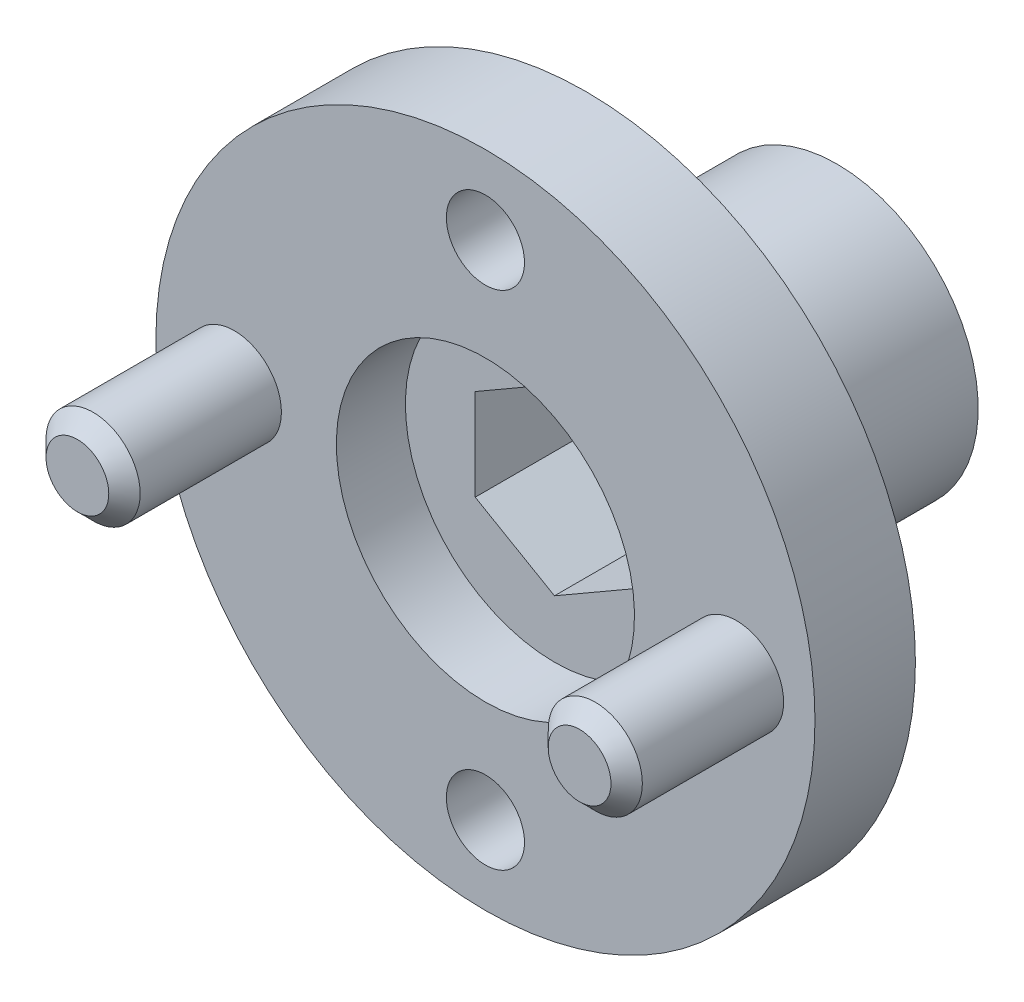
SolidWorks part; units mm, degrees
ref_plane "Front Plane" through (0, 0, 0) normal (0, 0, 1) x (1, 0, 0)
ref_plane "Top Plane" through (0, 0, 0) normal (0, 1, 0) x (1, 0, 0)
ref_plane "Right Plane" through (0, 0, 0) normal (1, 0, 0) x (0, 0, -1)
ref_plane "Plane1" through (0, 0, 0) normal (0, -1, 0) x (1, 0, 0)
sketch "Sketch1" plane through (0, 0, 0) normal (0, -1, 0) x (1, 0, 0)
  line L0 (10.5, 0) -> (0, 0)
  line L1 (0, 0) -> (0, -3.2)
  line L2 (0, -3.2) -> (10.5, -3.2)
  line L3 (10.5, -3.2) -> (10.5, 0)
  line L4 (0, 0) -> (0, -3.2) construction
revolve "Revolve1" add sketch "Sketch1" angle 360 about L4
sketch "Sketch2" plane through (0, 0, -3.2) normal (0, 0, -1) x (-1, 0, 0)
  circle A0 centre (0, 0) radius 6
extrude "Boss-Extrude1" add sketch "Sketch2" along normal blind 1
sketch "Sketch3" plane through (0, 0, -4.2) normal (0, 0, -1) x (-1, 0, 0)
  circle A0 centre (0, 0) radius 4.5
extrude "Boss-Extrude2" add sketch "Sketch3" along normal blind 7
sketch "Sketch4" plane through (0, 0, 0) normal (0, 0, 1) x (1, 0, 0)
  line L0 (2.525, -1.4578) -> (2.525, 1.4578)
  line L1 (2.525, 1.4578) -> (0, 2.9156)
  line L2 (0, 2.9156) -> (-2.525, 1.4578)
  line L3 (-2.525, 1.4578) -> (-2.525, -1.4578)
  line L4 (-2.525, -1.4578) -> (0, -2.9156)
  line L5 (0, -2.9156) -> (2.525, -1.4578)
extrude "Cut-Extrude1" cut sketch "Sketch4" against normal through all
sketch "Sketch5" plane through (0, 0, 0) normal (1, 0, 0) x (0, 0, -1)
  line L0 (2.2, -4.75) -> (2.2, 0)
  line L1 (2.2, 0) -> (0, 0)
  line L2 (0, 0) -> (0, -4.75)
  line L3 (0, -4.75) -> (2.2, -4.75)
  line L4 (2.2, 0) -> (0, 0) construction
revolve "Cut-Revolve1" cut sketch "Sketch5" angle 360 about L4
sketch "Sketch6" plane through (0, 0, 0) normal (0, 1, 0) x (1, 0, 0)
  line L0 (-6.5, 0) -> (-8, 0)
  line L1 (-8, 0) -> (-8, -5)
  line L2 (-8, -5) -> (-6.5, -5)
  line L3 (-6.5, -5) -> (-6.5, 0)
  line L4 (-8, 0) -> (-8, -5) construction
revolve "Revolve2" add sketch "Sketch6" angle 360 about L4
sketch "Sketch7" plane through (0, 0, 0) normal (0, 1, 0) x (1, 0, 0)
  line L0 (9.5, 0) -> (8, 0)
  line L1 (8, 0) -> (8, -5)
  line L2 (8, -5) -> (9.5, -5)
  line L3 (9.5, -5) -> (9.5, 0)
  line L4 (8, 0) -> (8, -5) construction
revolve "Revolve3" add sketch "Sketch7" angle 360 about L4
hole_wizard "M2 Clearance Hole1" positions "Sketch9" profile "Sketch8" hole size "M2" standard "ANSI Metric"
sketch "Sketch9" plane through (0, 0, 0) normal (0, 0, 1) x (1, 0, 0)
  point P0 (0, -8)
  point P1 (0, 8)
sketch "Sketch8" plane through (0, -8, 0) normal (1, 0, 0) x (0, -1, 0)
  line L0 (0, 0) -> (0, 11.2)
  line L1 (0, 11.2) -> (1.245, 11.2)
  line L2 (1.245, 11.2) -> (1.245, 0)
  line L5 (1.245, 0) -> (0, 0)
  line L11 (0, -6.35) -> (0, 107.95) construction
  dimension "Thru Hole Dia." = 2.49
  dimension "Thru Hole Depth" = 11.2
chamfer "Chamfer1" distance 0.5 angle 45 2 edges at (-6.5, 0, 5) (9.5, 0, 5)
